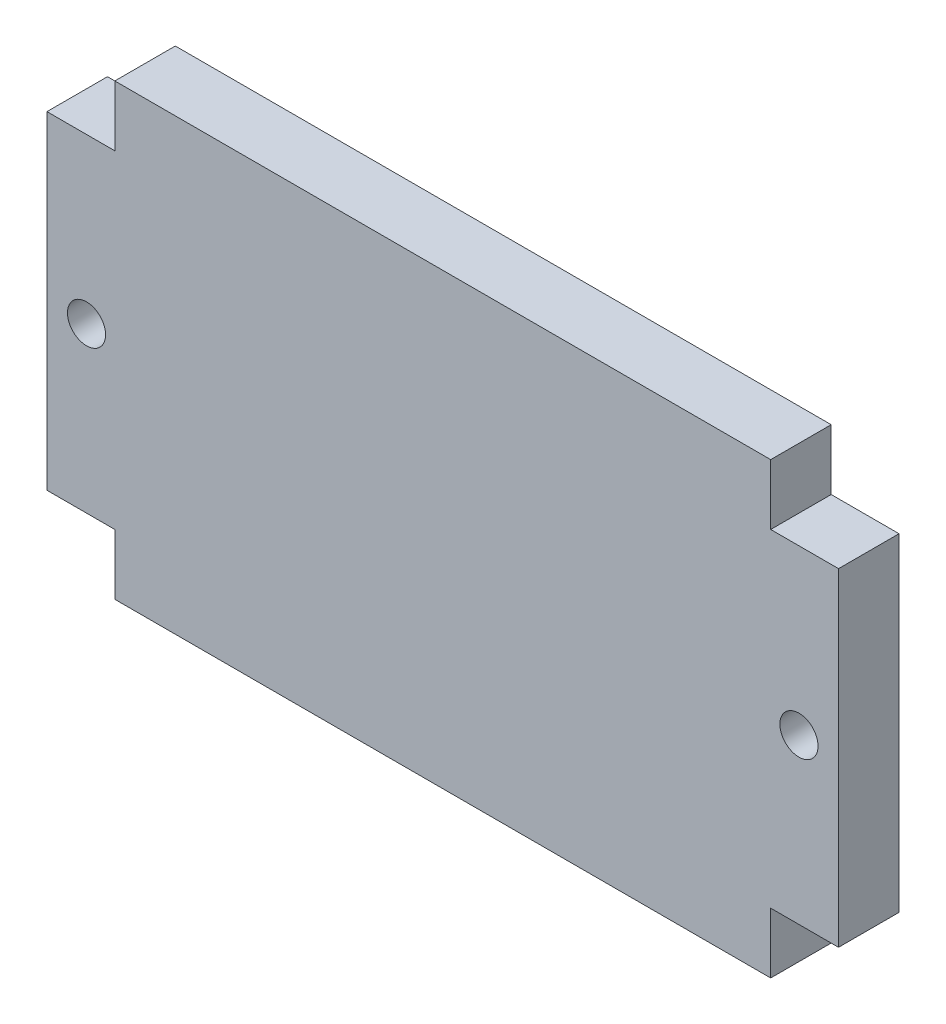
SolidWorks part; units mm, degrees
ref_plane "Front Plane" through (0, 0, 0) normal (0, 0, 1) x (1, 0, 0)
ref_plane "Top Plane" through (0, 0, 0) normal (0, 1, 0) x (1, 0, 0)
ref_plane "Right Plane" through (0, 0, 0) normal (1, 0, 0) x (0, 0, -1)
sketch "Model" plane through (0, 0, 0) normal (0, 0, 1) x (1, 0, 0)
  line L368 (6, 5.35) -> (6, 0)
  line L369 (0, 5.35) -> (6, 5.35)
  line L370 (0, 34.35) -> (0, 5.35)
  line L371 (6, 34.35) -> (0, 34.35)
  line L372 (6, 39.7) -> (6, 34.35)
  line L373 (64, 39.7) -> (6, 39.7)
  line L374 (64, 34.35) -> (64, 39.7)
  line L375 (70, 34.35) -> (64, 34.35)
  line L376 (70, 5.35) -> (70, 34.35)
  line L377 (64, 5.35) -> (70, 5.35)
  line L378 (64, 0) -> (64, 5.35)
  line L379 (6, 0) -> (64, 0)
  circle A52 centre (66.5, 19.85) radius 1.685
  circle A53 centre (3.5, 19.85) radius 1.685
extrude "Boss-Extrude1" add sketch "Model" along normal blind 5.35
